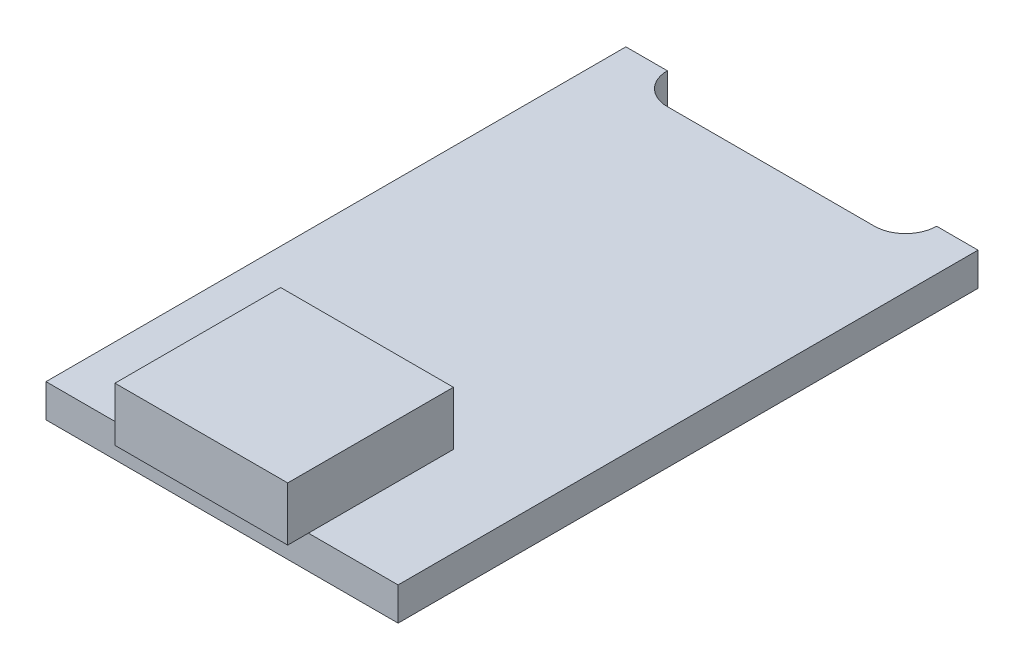
SolidWorks part; units mm, degrees
ref_plane "Front Plane" through (0, 0, 0) normal (0, 0, 1) x (1, 0, 0)
ref_plane "Top Plane" through (0, 0, 0) normal (0, 1, 0) x (1, 0, 0)
ref_plane "Right Plane" through (0, 0, 0) normal (1, 0, 0) x (0, 0, -1)
sketch "Sketch1" plane through (0, 0, 0) normal (0, 1, 0) x (1, 0, 0)
  line L0 (-126.8811, -95.6642) -> (-126.8811, 348.2006) construction
  line L1 (-8.5, -14) -> (8.5, -14)
  line L2 (-8.5, -14) -> (-8.5, 14)
  line L3 (-8.5, 14) -> (8.5, 14)
  line L4 (8.5, -14) -> (8.5, 14)
  line L5 (-8.5, -14) -> (8.5, 14) construction
  line L6 (-8.5, 14) -> (8.5, -14) construction
  point P0 (0, 0)
extrude "Boss-Extrude1" add sketch "Sketch1" along normal blind 1.6
sketch "Sketch2" plane through (0, 1.6, 0) normal (0, 1, 0) x (1, 0, 0)
  line L0 (-8.5, -14) -> (8.5, -14) construction
  line L1 (-4.17, -7) -> (4.17, -7)
  line L2 (-4.17, -7) -> (-4.17, -15)
  line L3 (-4.17, -15) -> (4.17, -15)
  line L4 (4.17, -7) -> (4.17, -15)
  line L5 (-4.17, -7) -> (4.17, -15) construction
  line L6 (-4.17, -15) -> (4.17, -7) construction
  point P0 (0, -11)
  dimension "D1" = 8.34
  dimension "D2" = 8
  dimension "D3" = 1
extrude "Boss-Extrude2" add sketch "Sketch2" along normal blind 2.6
sketch "Sketch3" plane through (0, 1.6, 0) normal (0, 1, 0) x (1, 0, 0)
  line L0 (-5, 14) -> (5, 14) construction
  line L1 (8.5, 14) -> (-8.5, 14) construction
  line L2 (-5, 15.5) -> (5, 15.5)
  line L3 (-5, 12.5) -> (5, 12.5)
  line L4 (274.347, -738.5838) -> (274.347, -135.9171) construction
  arc A0 (-5, 15.5) -> (-5, 12.5) centre (-5, 14) ccw
  arc A1 (5, 12.5) -> (5, 15.5) centre (5, 14) ccw
  point P4 (0, 14)
  dimension "D2" = 1.5
  dimension "D1" = 10
extrude "Cut-Extrude1" cut sketch "Sketch3" against normal through all
